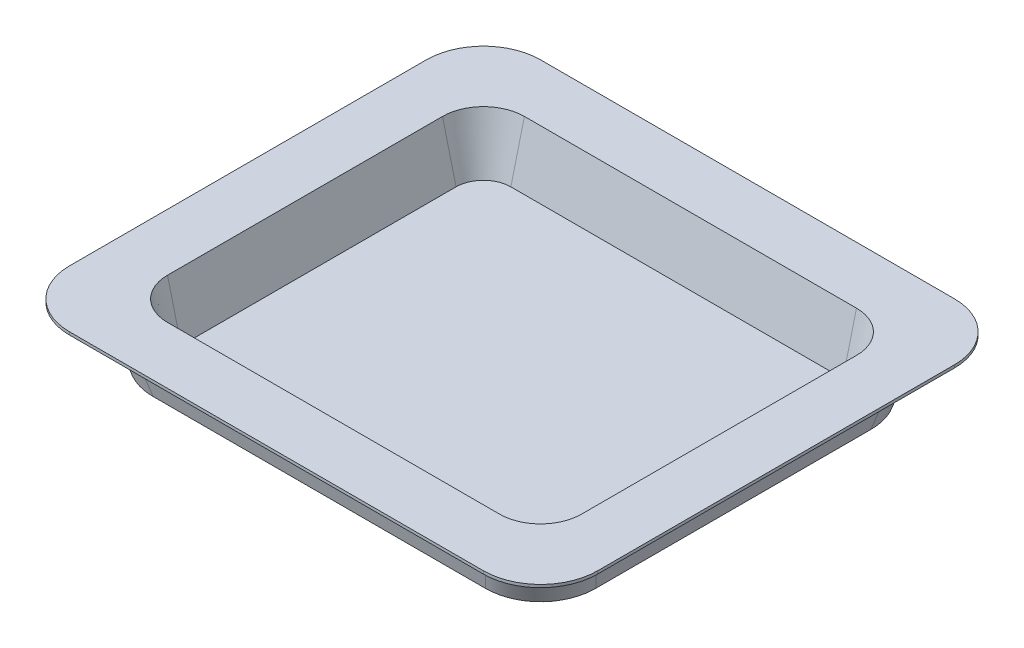
SolidWorks part; units mm, degrees
ref_plane "Alzado" through (0, 0, 0) normal (0, 0, 1) x (1, 0, 0)
ref_plane "Planta" through (0, 0, 0) normal (0, 1, 0) x (1, 0, 0)
ref_plane "Vista lateral" through (0, 0, 0) normal (1, 0, 0) x (0, 0, -1)
sketch "Sketch8" plane through (0, 0, 0) normal (0, 1, 0) x (1, 0, 0)
  line L0 (-71.8259, 380.3952) -> (-71.8259, -38.7048)
  line L1 (-71.8259, 380.3952) -> (398.0741, 380.3952)
  line L2 (398.0741, 380.3952) -> (398.0741, -38.7048)
  line L3 (398.0741, -38.7048) -> (-71.8259, -38.7048)
extrude "Boss-Extrude1" add sketch "Sketch8" against normal blind 50.8
sketch "Sketch9" plane through (0, 0, 0) normal (0, 1, 0) x (1, 0, 0)
  line L2 (398.0741, -38.7048) -> (398.0741, 380.3952) construction
  line L3 (398.0741, 380.3952) -> (-71.8259, 380.3952)
  line L5 (398.0741, -38.7048) -> (-71.8259, -38.7048)
  line L9 (-71.8259, -38.7048) -> (-46.4259, -13.3048)
  line L10 (398.0741, -38.7048) -> (372.6741, -13.3048)
  line L11 (-46.4259, -13.3048) -> (372.6741, -13.3048)
  line L13 (-46.4259, 354.9952) -> (372.6741, 354.9952)
extrude "Cut-Extrude3" cut sketch "Sketch9" against normal blind 48.26 contours L11 L9 L5 L10
sketch "Sketch11" plane through (0, 0, 0) normal (0, 1, 0) x (1, 0, 0)
  line L0 (-46.4259, 354.9952) -> (-46.4259, -13.3048)
  line L1 (-71.8259, 380.3952) -> (-46.4259, 354.9952)
  line L2 (-71.8259, 380.3952) -> (-71.8259, -38.7048)
  line L3 (-46.4259, -13.3048) -> (-71.8259, -38.7048)
extrude "Cut-Extrude4" cut sketch "Sketch11" against normal blind 48.26
sketch "Sketch13" plane through (0, 0, 0) normal (0, 1, 0) x (1, 0, 0)
  line L0 (-46.4259, 354.9952) -> (372.6741, 354.9952)
  line L1 (-46.4259, 354.9952) -> (-71.8259, 380.3952)
  line L2 (-71.8259, 380.3952) -> (398.0741, 380.3952)
  line L3 (398.0741, 380.3952) -> (372.6741, 354.9952)
extrude "Cut-Extrude5" cut sketch "Sketch13" against normal blind 48.26
sketch "Sketch14" plane through (0, 0, 0) normal (0, 1, 0) x (1, 0, 0)
  line L0 (398.0741, 380.3952) -> (372.6741, 354.9952)
  line L1 (372.6741, 354.9952) -> (372.6741, -13.3048)
  line L2 (372.6741, -13.3048) -> (398.0741, -38.7048)
  line L3 (398.0741, -38.7048) -> (398.0741, 380.3952)
extrude "Cut-Extrude6" cut sketch "Sketch14" against normal blind 48.26
sketch "Sketch16" plane through (0, 0, 0) normal (0, 0, 1) x (1, 0, 0)
  line L0 (-46.4259, 0) -> (-33.7259, 0)
  line L1 (-46.4259, 0) -> (372.6741, 0) construction
  line L2 (-46.4259, 0) -> (-46.4259, -48.26)
  line L3 (-46.4259, -48.26) -> (-33.7259, 0)
extrude "Cut-Extrude7" cut sketch "Sketch16" against normal blind 416.052
sketch "Sketch17" plane through (0, 0, 0) normal (0, 0, 1) x (1, 0, 0)
  line L0 (-33.7259, 0) -> (-46.4259, 0)
  line L1 (-46.4259, 0) -> (-46.4259, -48.26)
  line L2 (-46.4259, -48.26) -> (-33.7259, 0)
extrude "Cut-Extrude8" cut sketch "Sketch17" along normal blind 69.342
sketch "Sketch18" plane through (0, 0, 0) normal (0, 0, 1) x (1, 0, 0)
  line L0 (372.6741, 0) -> (359.9741, 0)
  line L1 (-33.7259, 0) -> (372.6741, 0) construction
  line L2 (359.9741, 0) -> (372.6741, -48.26)
  line L3 (372.6741, -48.26) -> (372.6741, 0)
extrude "Cut-Extrude9" cut sketch "Sketch18" against normal blind 516.128 and the other way blind 104.902
sketch "Sketch19" plane through (0, 0, 0) normal (1, 0, 0) x (0, 0, -1)
  line L0 (-13.3048, 0) -> (-0.6048, 0)
  line L1 (-13.3048, 0) -> (354.9952, 0) construction
  line L2 (-0.6048, 0) -> (-13.3048, -48.26)
  line L3 (-13.3048, -48.26) -> (-13.3048, 0)
extrude "Cut-Extrude10" cut sketch "Sketch19" along normal blind 483.87 and the other way blind 154.432
sketch "Sketch20" plane through (0, 0, 0) normal (1, 0, 0) x (0, 0, -1)
  line L0 (354.9952, 0) -> (342.2952, 0)
  line L1 (-0.6048, 0) -> (354.9952, 0) construction
  line L2 (342.2952, 0) -> (354.9952, -48.26)
  line L3 (354.9952, -48.26) -> (354.9952, 0)
extrude "Cut-Extrude11" cut sketch "Sketch20" against normal blind 113.03 and the other way blind 419.608
fillet "Fillet1" radius 50.8 1 edges at (-40.0759, -24.13, 6.9548)
fillet "Fillet2" radius 50.8 1 edges at (-40.0759, -24.13, -348.6452)
fillet "Fillet3" radius 50.8 1 edges at (366.3241, -24.13, -348.6452)
fillet "Fillet4" radius 50.8 1 edges at (366.3241, -24.13, 6.9548)
sketch "Sketch24" plane through (0, 0, 0) normal (0, 1, 0) x (1, 0, 0)
  line L0 (-71.8259, -38.7048) -> (-21.0259, -38.7048)
  line L1 (-71.8259, -38.7048) -> (-71.8259, 12.0952)
  arc A0 (-71.8259, 12.0952) -> (-21.0259, -38.7048) centre (-21.0259, 12.0952) ccw
extrude "Cut-Extrude12" cut sketch "Sketch24" against normal blind 113.03
sketch "Sketch25" plane through (0, 0, 0) normal (0, 1, 0) x (1, 0, 0)
  line L0 (-71.8259, 380.3952) -> (-21.0259, 380.3952)
  line L1 (-71.8259, 380.3952) -> (-71.8259, 329.5952)
  arc A0 (-21.0259, 380.3952) -> (-71.8259, 329.5952) centre (-21.0259, 329.5952) ccw
extrude "Cut-Extrude13" cut sketch "Sketch25" against normal blind 113.03
sketch "Sketch26" plane through (0, 0, 0) normal (0, 1, 0) x (1, 0, 0)
  line L0 (398.0741, 380.3952) -> (347.2741, 380.3952)
  line L1 (398.0741, 380.3952) -> (398.0741, 329.5952)
  arc A0 (398.0741, 329.5952) -> (347.2741, 380.3952) centre (347.2741, 329.5952) ccw
extrude "Cut-Extrude14" cut sketch "Sketch26" against normal blind 113.03
sketch "Sketch27" plane through (0, 0, 0) normal (0, 1, 0) x (1, 0, 0)
  line L0 (398.0741, -38.7048) -> (347.2741, -38.7048)
  line L1 (398.0741, -38.7048) -> (398.0741, 12.0952)
  arc A0 (347.2741, -38.7048) -> (398.0741, 12.0952) centre (347.2741, 12.0952) ccw
extrude "Cut-Extrude15" cut sketch "Sketch27" against normal blind 113.03
sketch "Sketch29" plane through (0, -50.8, 0) normal (0, 1, 0) x (1, 0, 0)
  line L3 (310.8467, 12.0952) -> (15.4015, 12.0952)
  line L7 (15.4015, 329.5952) -> (310.8467, 329.5952)
  line L9 (-21.0259, 293.1679) -> (-21.0259, 48.5226)
  line L11 (347.2741, 293.1679) -> (347.2741, 48.5226)
  arc A0 (15.4015, 329.5952) -> (-21.0259, 293.1679) centre (15.4015, 293.1679) ccw
  arc A1 (310.8467, 329.5952) -> (347.2741, 293.1679) centre (310.8467, 293.1679) cw
  arc A2 (15.4015, 12.0952) -> (-21.0259, 48.5226) centre (15.4015, 48.5226) cw
  arc A3 (310.8467, 12.0952) -> (347.2741, 48.5226) centre (310.8467, 48.5226) ccw
extrude "Cut-Extrude18" cut sketch "Sketch29" along normal blind 48.26 draft 14
move or copy body "Body-Move/Copy1" bodies to move or copy 118 copy no rotation origin (163.1241, -25.4, 0) rotation axis (0, 0, 1) rotation angle 180
